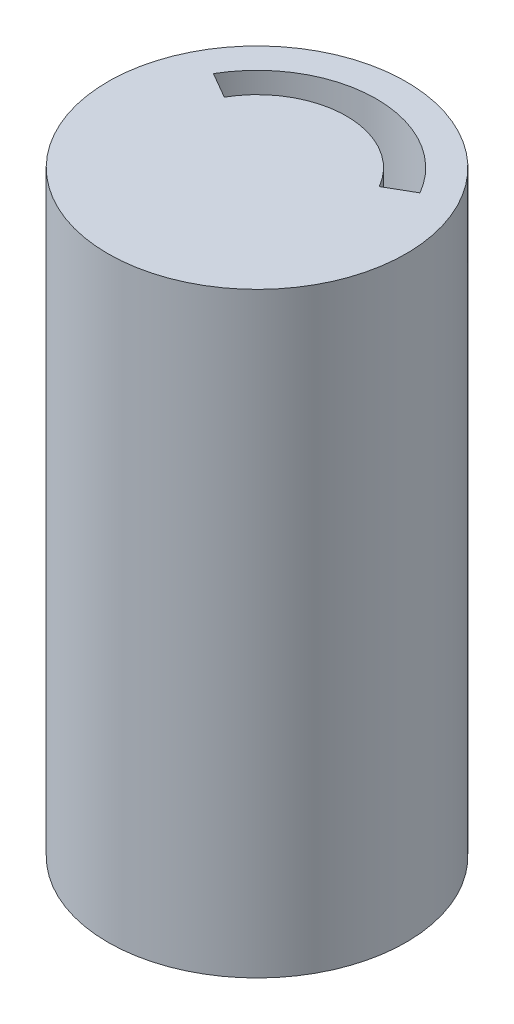
SolidWorks part; units mm, degrees
ref_plane "Front Plane" through (0, 0, 0) normal (0, 0, 1) x (1, 0, 0)
ref_plane "Top Plane" through (0, 0, 0) normal (0, 1, 0) x (1, 0, 0)
ref_plane "Right Plane" through (0, 0, 0) normal (1, 0, 0) x (0, 0, -1)
sketch "Sketch1" plane through (0, 0, 0) normal (0, 1, 0) x (1, 0, 0)
  line L0 (0, 0) -> (0, 5) construction
  line L1 (0, 0) -> (4.3301, 2.5) construction
  line L2 (0, 0) -> (-4.3301, 2.5) construction
  line L3 (-3.4641, 2) -> (-2.5981, 1.5)
  line L4 (2.5981, 1.5) -> (3.4641, 2)
  circle A0 centre (0, 0) radius 5
  arc A1 (-2.5981, 1.5) -> (2.5981, 1.5) centre (0, 0) cw
  arc A2 (-3.4641, 2) -> (3.4641, 2) centre (0, 0) cw
  dimension "D1" = 10
  dimension "D3" = 3
  dimension "D4" = 4
  dimension "D2" = 60
extrude "Boss-Extrude1" add sketch "Sketch1" along normal blind 20
sketch "Sketch2" plane through (0, 0, 0) normal (0, -1, 0) x (1, 0, 0)
  circle A0 centre (0, 0) radius 0.75
  dimension "D1" = 1.5
extrude "Cut-Extrude1" cut sketch "Sketch2" against normal blind 15
